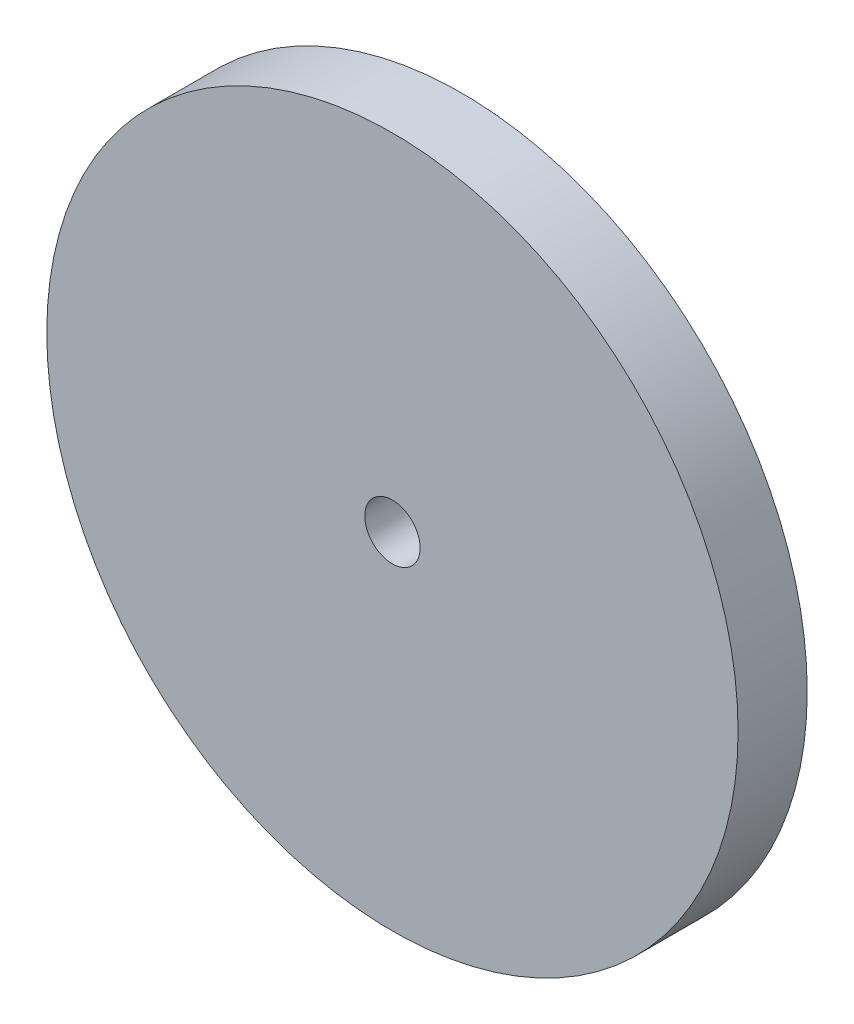
SolidWorks part; units mm, degrees
ref_plane "Front Plane" through (0, 0, 0) normal (0, 0, 1) x (1, 0, 0)
ref_plane "Top Plane" through (0, 0, 0) normal (0, 1, 0) x (1, 0, 0)
ref_plane "Right Plane" through (0, 0, 0) normal (1, 0, 0) x (0, 0, -1)
sketch "Sketch1" plane through (0, 0, 0) normal (0, 0, 1) x (1, 0, 0)
  circle A0 centre (0, 0) radius 50
  circle A1 centre (0, 0) radius 4
  dimension "D1" = 100
  dimension "D2" = 8
extrude "Boss-Extrude1" add sketch "Sketch1" along normal blind 10
